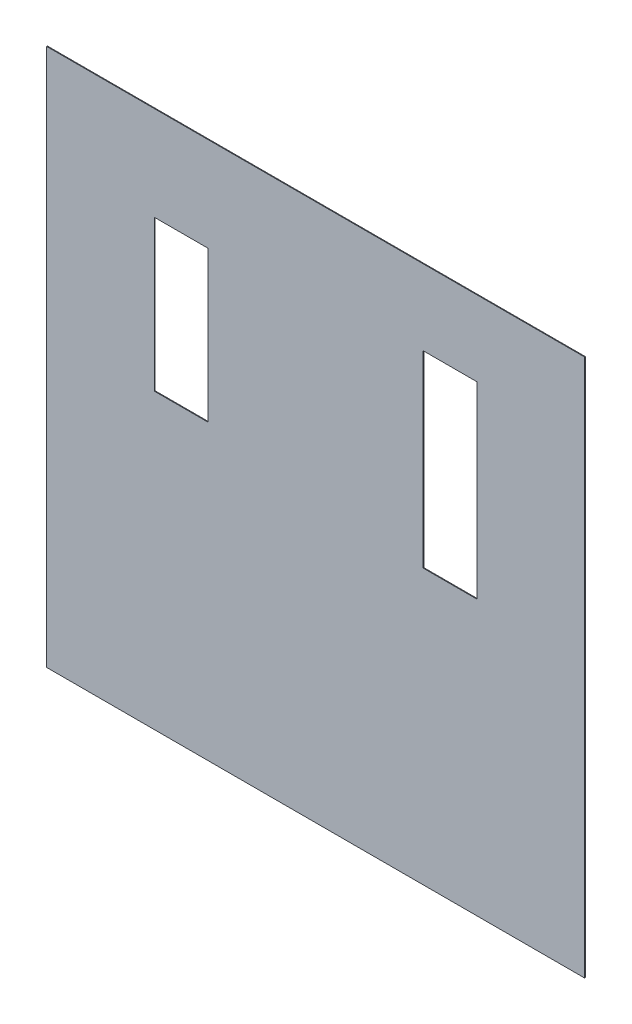
SolidWorks part; units mm, degrees
material "Copper"
ref_plane "Front Plane" through (0, 0, 0) normal (0, 0, 1) x (1, 0, 0)
ref_plane "Top Plane" through (0, 0, 0) normal (0, 1, 0) x (1, 0, 0)
ref_plane "Right Plane" through (0, 0, 0) normal (1, 0, 0) x (0, 0, -1)
sketch "Sketch1" plane through (0, 0, 0) normal (0, 0, 1) x (1, 0, 0)
  line L1 (0, 0) -> (25.4, 0)
  line L2 (0, 0) -> (0, 25.4)
  line L3 (0, 25.4) -> (25.4, 25.4)
  line L4 (25.4, 0) -> (25.4, 25.4)
  dimension "D1" = 25.4
  dimension "D2" = 25.4
extrude "Boss-Extrude1" add sketch "Sketch1" along normal blind 0.0356
sketch "Sketch2" plane through (0, 0, 0.0356) normal (0, 0, 1) x (1, 0, 0)
  line L0 (25.4, 25.4) -> (0, 25.4) construction
  line L1 (5.08, 20.955) -> (7.62, 20.955)
  line L2 (5.08, 20.955) -> (5.08, 13.843)
  line L3 (5.08, 13.843) -> (7.62, 13.843)
  line L4 (7.62, 20.955) -> (7.62, 13.843)
  line L5 (17.78, 21.844) -> (20.32, 21.844)
  line L6 (17.78, 21.844) -> (17.78, 12.954)
  line L7 (17.78, 12.954) -> (20.32, 12.954)
  line L8 (20.32, 21.844) -> (20.32, 12.954)
  point P10 (19.05, 12.954)
  point P11 (6.35, 13.843)
  point P12 (6.35, 20.955)
  point P13 (12.7, 25.4)
  dimension "D1" = 2.54
  dimension "D2" = 2.54
  dimension "D3" = 8.89
  dimension "D4" = 3.556
  dimension "D5" = 12.7
  dimension "D6" = 7.112
  dimension "D7" = 4.445
  dimension "D8" = 6.35
extrude "Cut-Extrude1" cut sketch "Sketch2" against normal through all
